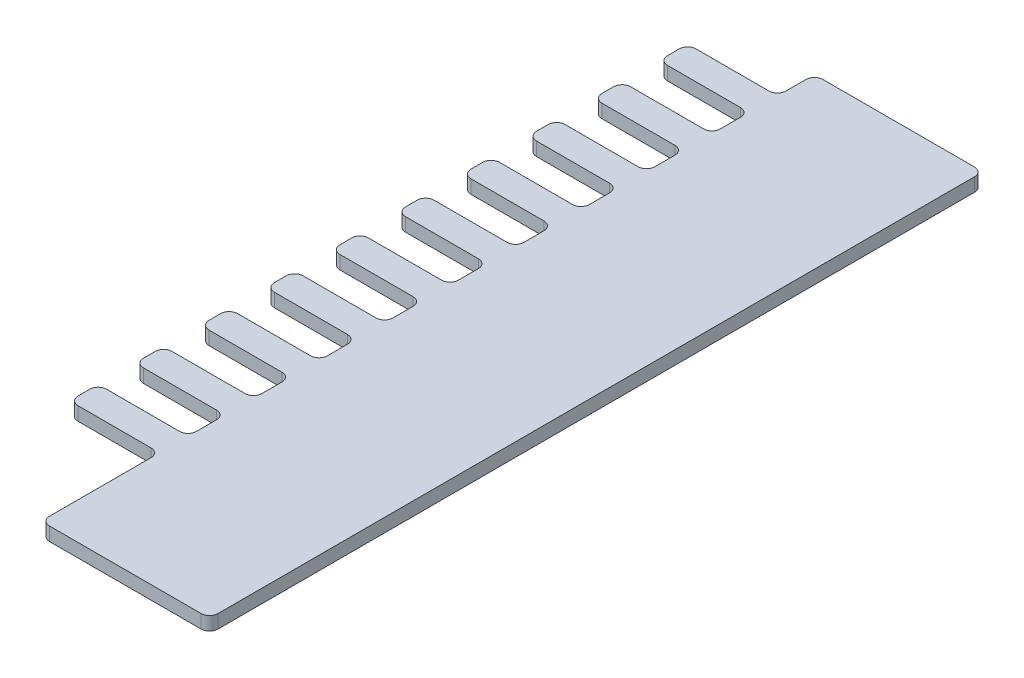
SolidWorks part; units mm, degrees
ref_plane "Front Plane" through (0, 0, 0) normal (0, 0, 1) x (1, 0, 0)
ref_plane "Top Plane" through (0, 0, 0) normal (0, 1, 0) x (1, 0, 0)
ref_plane "Right Plane" through (0, 0, 0) normal (1, 0, 0) x (0, 0, -1)
sketch "Sketch1" plane through (0, 0, 0) normal (0, 1, 0) x (1, 0, 0)
  line L0 (-0.75, 2.54) -> (-7.25, 2.54)
  line L2 (0, 1.79) -> (0, 0)
  line L5 (-8, 3.81) -> (5.7163, 3.81) construction
  line L7 (-8, 3.29) -> (-8, 4.33)
  line L8 (-7.25, 5.08) -> (-0.75, 5.08)
  line L12 (0, 7.62) -> (0, 5.83)
  line L17 (-0.75, 8.37) -> (-7.25, 8.37)
  line L22 (-8, 9.12) -> (-8, 10.16)
  line L27 (-7.25, 10.91) -> (-0.75, 10.91)
  line L32 (0, 13.45) -> (0, 11.66)
  line L37 (-0.75, 14.2) -> (-7.25, 14.2)
  line L42 (-8, 14.95) -> (-8, 15.99)
  line L47 (-7.25, 16.74) -> (-0.75, 16.74)
  line L52 (0, 19.28) -> (0, 17.49)
  line L53 (0, 58.3) -> (0, 60.09)
  line L54 (0.75, 60.84) -> (14.25, 60.84)
  line L55 (15, 60.09) -> (15, 0)
  line L56 (15, 0) -> (0, 0) construction
  line L57 (-0.75, 20.03) -> (-7.25, 20.03)
  line L58 (-8, 20.78) -> (-8, 21.82)
  line L59 (-7.25, 22.57) -> (-0.75, 22.57)
  line L60 (0, 25.11) -> (0, 23.32)
  line L61 (-0.75, 25.86) -> (-7.25, 25.86)
  line L62 (-8, 26.61) -> (-8, 27.65)
  line L63 (-7.25, 28.4) -> (-0.75, 28.4)
  line L64 (0, 30.94) -> (0, 29.15)
  line L65 (-0.75, 31.69) -> (-7.25, 31.69)
  line L66 (-8, 32.44) -> (-8, 33.48)
  line L67 (-7.25, 34.23) -> (-0.75, 34.23)
  line L68 (0, 36.77) -> (0, 34.98)
  line L69 (-0.75, 37.52) -> (-7.25, 37.52)
  line L70 (-8, 38.27) -> (-8, 39.31)
  line L71 (-7.25, 40.06) -> (-0.75, 40.06)
  line L72 (0, 42.6) -> (0, 40.81)
  line L73 (-0.75, 43.35) -> (-7.25, 43.35)
  line L74 (-8, 44.1) -> (-8, 45.14)
  line L75 (-7.25, 45.89) -> (-0.75, 45.89)
  line L76 (0, 48.43) -> (0, 46.64)
  line L77 (-0.75, 49.18) -> (-7.25, 49.18)
  line L78 (-8, 49.93) -> (-8, 50.97)
  line L79 (-7.25, 51.72) -> (-0.75, 51.72)
  line L80 (0, 54.26) -> (0, 52.47)
  line L81 (-0.75, 55.01) -> (-7.25, 55.01)
  line L82 (-8, 55.76) -> (-8, 56.8)
  line L83 (-7.25, 57.55) -> (-0.75, 57.55)
  line L84 (0, 0) -> (0, -7.25)
  line L85 (0.75, -8) -> (14.25, -8)
  line L86 (15, -7.25) -> (15, 0)
  arc A0 (-0.75, 5.08) -> (0, 5.83) centre (-0.75, 5.83) ccw
  arc A1 (-8, 4.33) -> (-7.25, 5.08) centre (-7.25, 4.33) cw
  arc A2 (-7.25, 2.54) -> (-8, 3.29) centre (-7.25, 3.29) cw
  arc A4 (-0.75, 2.54) -> (0, 1.79) centre (-0.75, 1.79) cw
  arc A6 (-0.75, 8.37) -> (0, 7.62) centre (-0.75, 7.62) cw
  arc A7 (-7.25, 8.37) -> (-8, 9.12) centre (-7.25, 9.12) cw
  arc A8 (-8, 10.16) -> (-7.25, 10.91) centre (-7.25, 10.16) cw
  arc A9 (-0.75, 10.91) -> (0, 11.66) centre (-0.75, 11.66) ccw
  arc A10 (-0.75, 14.2) -> (0, 13.45) centre (-0.75, 13.45) cw
  arc A11 (-7.25, 14.2) -> (-8, 14.95) centre (-7.25, 14.95) cw
  arc A12 (-8, 15.99) -> (-7.25, 16.74) centre (-7.25, 15.99) cw
  arc A13 (-0.75, 16.74) -> (0, 17.49) centre (-0.75, 17.49) ccw
  arc A14 (-0.75, 20.03) -> (0, 19.28) centre (-0.75, 19.28) cw
  arc A15 (-7.25, 20.03) -> (-8, 20.78) centre (-7.25, 20.78) cw
  arc A16 (-8, 21.82) -> (-7.25, 22.57) centre (-7.25, 21.82) cw
  arc A17 (-0.75, 22.57) -> (0, 23.32) centre (-0.75, 23.32) ccw
  arc A18 (-0.75, 25.86) -> (0, 25.11) centre (-0.75, 25.11) cw
  arc A19 (-7.25, 25.86) -> (-8, 26.61) centre (-7.25, 26.61) cw
  arc A20 (-8, 27.65) -> (-7.25, 28.4) centre (-7.25, 27.65) cw
  arc A21 (-0.75, 28.4) -> (0, 29.15) centre (-0.75, 29.15) ccw
  arc A22 (-0.75, 31.69) -> (0, 30.94) centre (-0.75, 30.94) cw
  arc A23 (-7.25, 31.69) -> (-8, 32.44) centre (-7.25, 32.44) cw
  arc A24 (-8, 33.48) -> (-7.25, 34.23) centre (-7.25, 33.48) cw
  arc A25 (-0.75, 34.23) -> (0, 34.98) centre (-0.75, 34.98) ccw
  arc A26 (-0.75, 37.52) -> (0, 36.77) centre (-0.75, 36.77) cw
  arc A27 (-7.25, 37.52) -> (-8, 38.27) centre (-7.25, 38.27) cw
  arc A28 (-8, 39.31) -> (-7.25, 40.06) centre (-7.25, 39.31) cw
  arc A29 (-0.75, 40.06) -> (0, 40.81) centre (-0.75, 40.81) ccw
  arc A30 (-0.75, 43.35) -> (0, 42.6) centre (-0.75, 42.6) cw
  arc A31 (-7.25, 43.35) -> (-8, 44.1) centre (-7.25, 44.1) cw
  arc A32 (-8, 45.14) -> (-7.25, 45.89) centre (-7.25, 45.14) cw
  arc A33 (-0.75, 45.89) -> (0, 46.64) centre (-0.75, 46.64) ccw
  arc A34 (-0.75, 49.18) -> (0, 48.43) centre (-0.75, 48.43) cw
  arc A35 (-7.25, 49.18) -> (-8, 49.93) centre (-7.25, 49.93) cw
  arc A36 (-8, 50.97) -> (-7.25, 51.72) centre (-7.25, 50.97) cw
  arc A37 (-0.75, 51.72) -> (0, 52.47) centre (-0.75, 52.47) ccw
  arc A38 (-0.75, 55.01) -> (0, 54.26) centre (-0.75, 54.26) cw
  arc A39 (-7.25, 55.01) -> (-8, 55.76) centre (-7.25, 55.76) cw
  arc A40 (-8, 56.8) -> (-7.25, 57.55) centre (-7.25, 56.8) cw
  arc A41 (-0.75, 57.55) -> (0, 58.3) centre (-0.75, 58.3) ccw
  arc A42 (0, 60.09) -> (0.75, 60.84) centre (0.75, 60.09) cw
  arc A43 (14.25, 60.84) -> (15, 60.09) centre (14.25, 60.09) cw
  arc A44 (0, -7.25) -> (0.75, -8) centre (0.75, -7.25) ccw
  arc A45 (14.25, -8) -> (15, -7.25) centre (14.25, -7.25) ccw
  point P0 (0, 0)
  point P27 (0, 5.08)
  point P48 (-8, 5.08)
  point P69 (-8, 2.54)
  point P78 (0, 0)
  point P81 (0, 2.54)
  point P82 (7.5, -8)
  point P84 (15, 0)
  dimension "D6" = 0.75
  dimension "D7" = 0.75
  dimension "D8" = 0.75
  dimension "D9" = 0.75
  dimension "D1" = 2.54
  dimension "D2" = 8
  dimension "D3" = 10
  dimension "D4" = 2.54
  dimension "D5" = 15
  dimension "D10" = 8
extrude "Boss-Extrude1" add sketch "Sketch1" along normal blind 1.2
